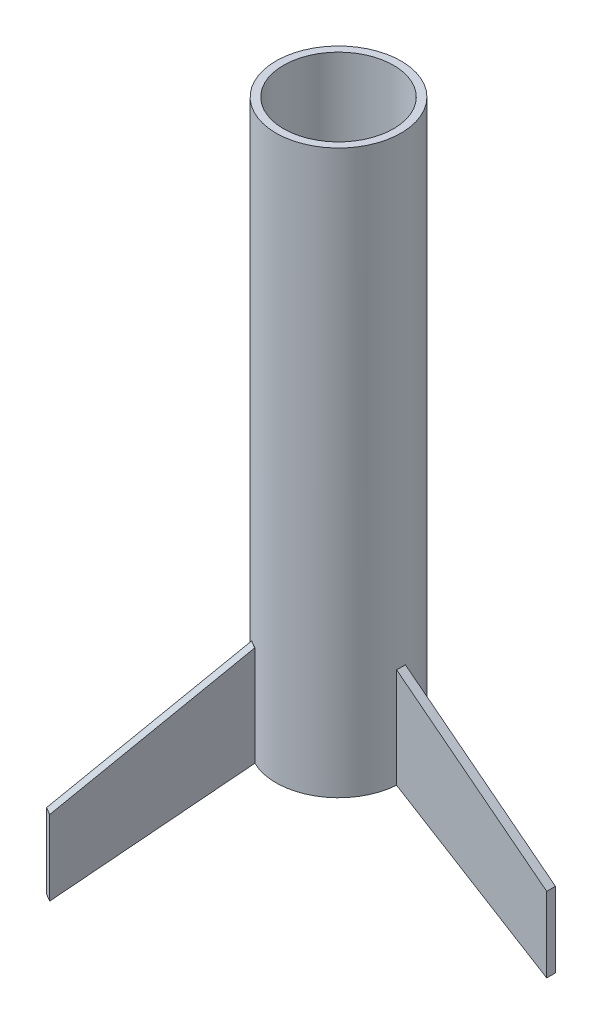
SolidWorks part; units mm, degrees
ref_plane "Front Plane" through (0, 0, 0) normal (0, 0, 1) x (1, 0, 0)
ref_plane "Top Plane" through (0, 0, 0) normal (0, 1, 0) x (1, 0, 0)
ref_plane "Right Plane" through (0, 0, 0) normal (1, 0, 0) x (0, 0, -1)
sketch "Sketch1" plane through (0, 0, 0) normal (0, 1, 0) x (1, 0, 0)
  circle A0 centre (0, 0) radius 11.176
  circle A1 centre (0, 0) radius 12.7
  dimension "D1" = 25.4
  dimension "D2" = 22.352
extrude "Boss-Extrude1" add sketch "Sketch1" along normal blind 114.3
sketch "Sketch2" plane through (0, 0, 0) normal (0, 0, 1) x (1, 0, 0)
  line L0 (12.7, 0) -> (11.176, 0)
  line L1 (11.176, 0) -> (11.176, 20.32)
  line L2 (11.176, 20.32) -> (12.7, 20.32)
  line L3 (12.7, 0) -> (12.7, 114.3) construction
  line L4 (12.7, 20.32) -> (43.18, -3.408)
  line L5 (43.18, -3.408) -> (43.18, -18.648)
  line L6 (43.18, -18.648) -> (12.7, 0)
  point P4 (0, 0)
  point P11 (0, 0)
  point P12 (0, 0)
  point P13 (0, 0)
  point P14 (0, 0)
  dimension "D1" = 15.24
  dimension "D2" = 20.32
  dimension "D3" = 30.48
  dimension "D4" = 52.1
extrude "Boss-Extrude2" add sketch "Sketch2" along normal mid plane 1.778
pattern_circular "CirPattern1" count 3 over 360 about axis through (0, 0, 0) along (0, 1, 0) of "Boss-Extrude2"
ref_plane "Plane2" through (0, 63.5, 0) normal (0, 1, 0) x (1, 0, 0)
sketch "Sketch3" plane through (0, 63.5, 0) normal (0, 1, 0) x (1, 0, 0)
  circle A0 centre (0, 0) radius 6.35
  circle A1 centre (0, 0) radius 11.176 construction
  circle A2 centre (0, 0) radius 11.176
  dimension "D1" = 12.7
extrude "Boss-Extrude3" add sketch "Sketch3" along normal blind 3.175
